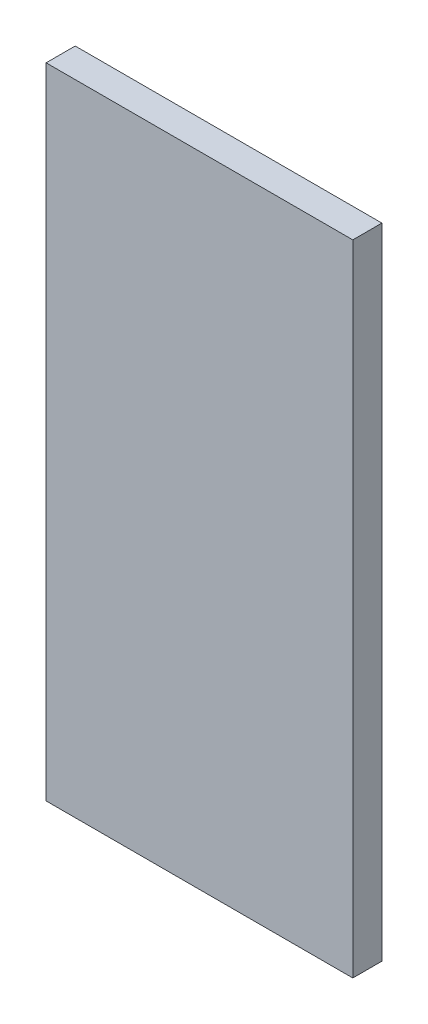
SolidWorks part; units mm, degrees
ref_plane "Ebene vorne" through (0, 0, 0) normal (0, 0, 1) x (1, 0, 0)
ref_plane "Ebene oben" through (0, 0, 0) normal (0, 1, 0) x (1, 0, 0)
ref_plane "Ebene rechts" through (0, 0, 0) normal (1, 0, 0) x (0, 0, -1)
sketch "Skizze1" plane through (0, 0, 0) normal (0, 0, 1) x (1, 0, 0)
  line L0 (-5.2705, 15.367) -> (5.2705, 15.367)
  line L1 (5.2705, 15.367) -> (5.2705, -6.604)
  line L2 (5.2705, -6.604) -> (-5.2705, -6.604)
  line L3 (-5.2705, -6.604) -> (-5.2705, 15.367)
extrude "Component_Outline" add sketch "Skizze1" along normal blind 1 separate body
sketch3d "3D-Skizze1"
  line L0 (0, 0, 0) -> (1, 0, 0)
  line L1 (0, 0, 0) -> (0, 1, 0)
  line L2 (0, 0, 0) -> (0, 0, 1)
  point P0 (0, 0, 0)
